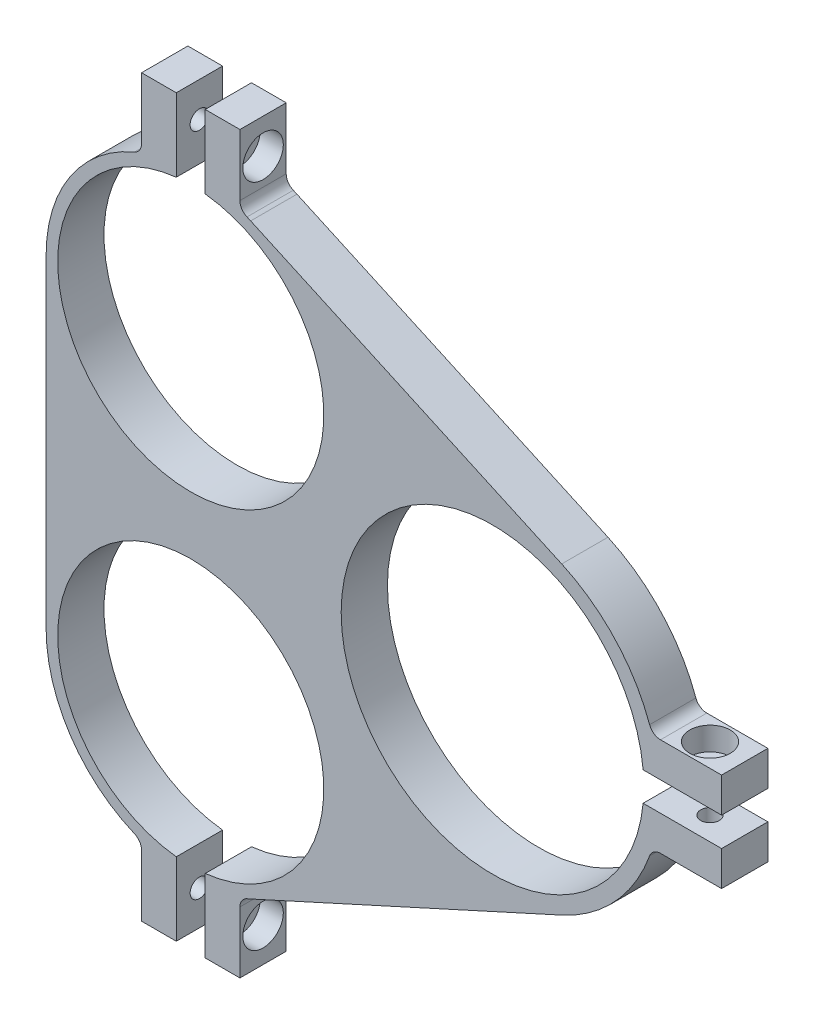
SolidWorks part; units mm, degrees
ref_plane "Front Plane" through (0, 0, 0) normal (0, 0, 1) x (1, 0, 0)
ref_plane "Top Plane" through (0, 0, 0) normal (0, 1, 0) x (1, 0, 0)
ref_plane "Right Plane" through (0, 0, 0) normal (1, 0, 0) x (0, 0, -1)
sketch "Sketch1" plane through (0, 0, 0) normal (0, 0, 1) x (1, 0, 0)
  line L0 (-39.6875, 88.9) -> (-39.6875, 0)
  line L1 (-39.6875, 44.45) -> (82.8036, 44.45) construction
  line L2 (16.439, 125.0228) -> (101.7939, 86.1791)
  line L3 (3.9688, -36.2962) -> (3.9688, -56.3731)
  line L4 (0, 88.9) -> (0, 0) construction
  line L5 (-13.4938, -37.3231) -> (-13.4938, -56.3731)
  line L6 (3.9688, -56.3731) -> (13.4938, -56.3731)
  line L7 (-3.9688, -56.3731) -> (-13.4938, -56.3731)
  line L8 (13.4938, -37.3231) -> (13.4938, -56.3731)
  line L9 (-3.9687, -36.2962) -> (-3.9688, -56.3731)
  line L10 (16.439, -36.1228) -> (101.7939, 2.7209)
  line L11 (13.4938, 126.2231) -> (13.4938, 145.2731)
  line L12 (-3.9688, 145.2731) -> (-13.4938, 145.2731)
  line L13 (3.9688, 145.2731) -> (13.4938, 145.2731)
  line L14 (3.9688, 145.2731) -> (3.9688, 125.1962)
  line L15 (-13.4938, 126.2231) -> (-13.4938, 145.2731)
  line L18 (-3.9688, 145.2731) -> (-3.9688, 125.1962)
  line L23 (3.9688, 145.2731) -> (-3.9688, 145.2731) construction
  line L25 (3.9688, -56.3731) -> (-3.9688, -56.3731) construction
  line L42 (124.1425, 48.4187) -> (145.6699, 48.4187)
  line L43 (145.6699, 48.4187) -> (145.6699, 57.9437)
  line L44 (145.6699, 57.9437) -> (126.6199, 57.9437)
  line L45 (124.1425, 40.4812) -> (145.6699, 40.4812)
  line L46 (145.6699, 40.4812) -> (145.6699, 30.9562)
  line L47 (145.6699, 30.9562) -> (126.6199, 30.9562)
  arc A0 (3.9688, -36.2962) -> (-3.9687, -36.2962) centre (0, 0) ccw
  arc A1 (-3.9688, 125.1962) -> (3.9688, 125.1962) centre (0, 88.9) ccw
  arc A2 (13.4938, 126.2231) -> (16.439, 125.0228) centre (0, 88.9) cw
  arc A3 (-39.6875, 0) -> (-13.4938, -37.3231) centre (0, 0) ccw
  arc A4 (124.1425, 48.4187) -> (124.1425, 40.4812) centre (82.8036, 44.45) ccw
  arc A5 (13.4938, -37.3231) -> (16.439, -36.1228) centre (0, 0) ccw
  arc A6 (-39.6875, 88.9) -> (-13.4938, 126.2231) centre (0, 88.9) cw
  arc A7 (126.6199, 57.9437) -> (126.6199, 30.9562) centre (82.8036, 44.45) ccw construction
  circle A8 centre (0, 0) radius 36.5125 construction
  circle A9 centre (0, 88.9) radius 36.5125 construction
  circle A10 centre (0, 0) radius 39.6875 construction
  circle A11 centre (82.8036, 44.45) radius 41.529 construction
  circle A12 centre (0, 88.9) radius 39.6875 construction
  arc A13 (101.7939, 86.1791) -> (126.6199, 57.9437) centre (82.8036, 44.45) cw
  circle A14 centre (77.8468, 40.4811) radius 32.004 construction
  circle A15 centre (82.8036, 44.45) radius 38.354 construction
  arc A18 (126.6199, 30.9562) -> (101.7939, 2.7209) centre (82.8036, 44.45) cw
  point P14 (0, 36.5125)
  point P36 (0, 0)
  point P38 (88.8822, 42.4655)
  dimension "D2" = 41.529
  dimension "D4" = 73.025
  dimension "D5" = 73.025
  dimension "D7" = 79.375
  dimension "D9" = 4.318
  dimension "D10" = 3.175
  dimension "D8" = 64.008
  dimension "D1" = 7.9375
  dimension "D3" = 88.9
  dimension "D6" = 9.525
  dimension "D12" = 93.98
  dimension "D17" = 9.525
  dimension "D18" = 7.9375
  dimension "D19" = 19.05
extrude "Extrude1" add sketch "Sketch1" along normal mid plane 12.7
hole_wizard "CBORE for 1/4 Socket Head Cap Screw1" positions "Sketch3" profile "Sketch2" counterbore size "1/4" standard "Ansi Inch"
sketch "Sketch3" plane through (13.4938, 0, 0) normal (1, 0, 0) x (0, 0, -1)
  line L0 (6.35, 145.2731) -> (-6.35, 126.2231) construction
  point P0 (0, 135.7481)
sketch "Sketch2" plane through (13.4938, 135.7481, 0) normal (0, 1, 0) x (0, 0, -1)
  line L0 (0, 0) -> (0, 9.525)
  line L1 (0, 9.525) -> (3.3782, 9.525)
  line L3 (3.3782, 9.525) -> (3.3782, 6.35)
  line L4 (3.3782, 6.35) -> (5.5562, 6.35)
  line L5 (5.5562, 6.35) -> (5.5562, 0)
  line L7 (5.5562, 0) -> (0, 0)
  line L11 (0, -6.35) -> (0, 107.95) construction
  dimension "Thru Hole Dia." = 6.7564
  dimension "Thru Hole Depth" = 9.525
  dimension "C'Bore Dia." = 11.1125
  dimension "C'Bore Depth" = 6.35
hole_wizard "1/4-20 Tapped Hole1" positions "Sketch5" profile "Sketch4" tap size "1/4-20" standard "Ansi Inch" end condition through all
sketch "Sketch5" plane through (-3.9688, 0, 0) normal (1, 0, 0) x (0, 0, -1)
  point P0 (0, 135.7481)
sketch "Sketch4" plane through (-3.9688, 135.7481, 0) normal (0, 1, 0) x (0, 0, -1)
  line L0 (0, 0) -> (0, 35.7188)
  line L1 (0, 35.7188) -> (2.5527, 35.7188)
  line L2 (2.5527, 35.7188) -> (2.5527, 0)
  line L5 (2.5527, 0) -> (0, 0)
  line L11 (0, -6.35) -> (0, 107.95) construction
  dimension "Thru Tap Drill Dia." = 5.1054
  dimension "Thru Tap Drill Depth" = 35.7188
cosmetic thread "Hole Thread1" parameters "D2"=6.35
hole_wizard "CBORE for 1/4 Socket Head Cap Screw3" positions "Sketch16" profile "Sketch17" counterbore size "1/4" standard "Ansi Inch"
sketch "Sketch16" plane through (13.4938, 0, 0) normal (1, 0, 0) x (0, 0, -1)
  line L0 (6.35, -37.3231) -> (-6.35, -56.3731) construction
  point P0 (0, -46.8481)
sketch "Sketch17" plane through (13.4938, -46.8481, 0) normal (0, 1, 0) x (0, 0, -1)
  line L0 (0, 0) -> (0, 9.525)
  line L1 (0, 9.525) -> (3.3782, 9.525)
  line L3 (3.3782, 9.525) -> (3.3782, 6.35)
  line L4 (3.3782, 6.35) -> (5.5562, 6.35)
  line L5 (5.5562, 6.35) -> (5.5562, 0)
  line L7 (5.5562, 0) -> (0, 0)
  line L11 (0, -6.35) -> (0, 107.95) construction
  dimension "Thru Hole Dia." = 6.7564
  dimension "Thru Hole Depth" = 9.525
  dimension "C'Bore Dia." = 11.1125
  dimension "C'Bore Depth" = 6.35
hole_wizard "1/4-20 Tapped Hole4" positions "Sketch19" profile "Sketch21" tap size "1/4-20" standard "Ansi Inch" end condition through all
sketch "Sketch19" plane through (-3.9687, 0, 0) normal (1, 0, 0) x (0, 0, -1)
  point P0 (0, -46.8481)
sketch "Sketch21" plane through (-3.9687, -46.8481, 0) normal (0, 1, 0) x (0, 0, -1)
  line L0 (0, 0) -> (0, 35.7188)
  line L1 (0, 35.7188) -> (2.5527, 35.7188)
  line L2 (2.5527, 35.7188) -> (2.5527, 0)
  line L5 (2.5527, 0) -> (0, 0)
  line L11 (0, -6.35) -> (0, 107.95) construction
  dimension "Thru Tap Drill Dia." = 5.1054
  dimension "Thru Tap Drill Depth" = 35.7188
cosmetic thread "Hole Thread4" parameters "D2"=6.35
sketch "Sketch41" plane through (0, 57.9437, 0) normal (0, 1, 0) x (1, 0, 0)
  line L0 (145.6699, 6.35) -> (126.6199, -6.35) construction
hole_wizard "CBORE for 1/4 Socket Head Cap Screw6" positions "Sketch42" profile "Sketch43" counterbore size "1/4" standard "ANSI Inch"
sketch "Sketch42" plane through (0, 57.9437, 0) normal (0, 1, 0) x (1, 0, 0)
  line L0 (145.6699, 6.35) -> (126.6199, -6.35) construction
  point P0 (136.1449, 0)
sketch "Sketch43" plane through (136.1449, 57.9437, 0) normal (1, 0, 0) x (0, 0, 1)
  line L0 (0, 0) -> (0, 9.525)
  line L1 (0, 9.525) -> (3.3782, 9.525)
  line L3 (3.3782, 9.525) -> (3.3782, 6.35)
  line L4 (3.3782, 6.35) -> (5.5562, 6.35)
  line L5 (5.5562, 6.35) -> (5.5563, 0)
  line L7 (5.5563, 0) -> (0, 0)
  line L11 (0, -6.35) -> (0, 107.95) construction
  dimension "Thru Hole Dia." = 6.7564
  dimension "Thru Hole Depth" = 9.525
  dimension "C'Bore Dia." = 11.1125
  dimension "C'Bore Depth" = 6.35
hole_wizard "1/4-20 Tapped Hole7" positions "Sketch44" profile "Sketch45" tap size "1/4-20" standard "ANSI Inch" end condition up to next
sketch "Sketch44" plane through (0, 40.4812, 0) normal (0, 1, 0) x (1, 0, 0)
  line L0 (145.6699, 6.35) -> (126.6199, -6.35) construction
  point P0 (136.1449, 0)
sketch "Sketch45" plane through (136.1449, 40.4812, 0) normal (1, 0, 0) x (0, 0, 1)
  line L0 (0, 0) -> (0, 9.525)
  line L1 (0, 9.525) -> (2.5527, 9.525)
  line L2 (2.5527, 9.525) -> (2.5527, 0)
  line L5 (2.5527, 0) -> (0, 0)
  line L11 (0, -6.35) -> (0, 107.95) construction
  dimension "Thru Tap Drill Dia." = 5.1054
  dimension "Thru Tap Drill Depth" = 9.525
cosmetic thread "Hole Thread7" parameters "D2"=6.35
fillet "Fillet1" radius 3.175 6 edges at (13.4938, 126.2231, 0) (-13.4938, 126.2231, 0) (-13.4938, -37.3231, 0) (13.4938, -37.3231, 0) (126.6199, 30.9563, 0) (126.6199, 57.9437, 0)
